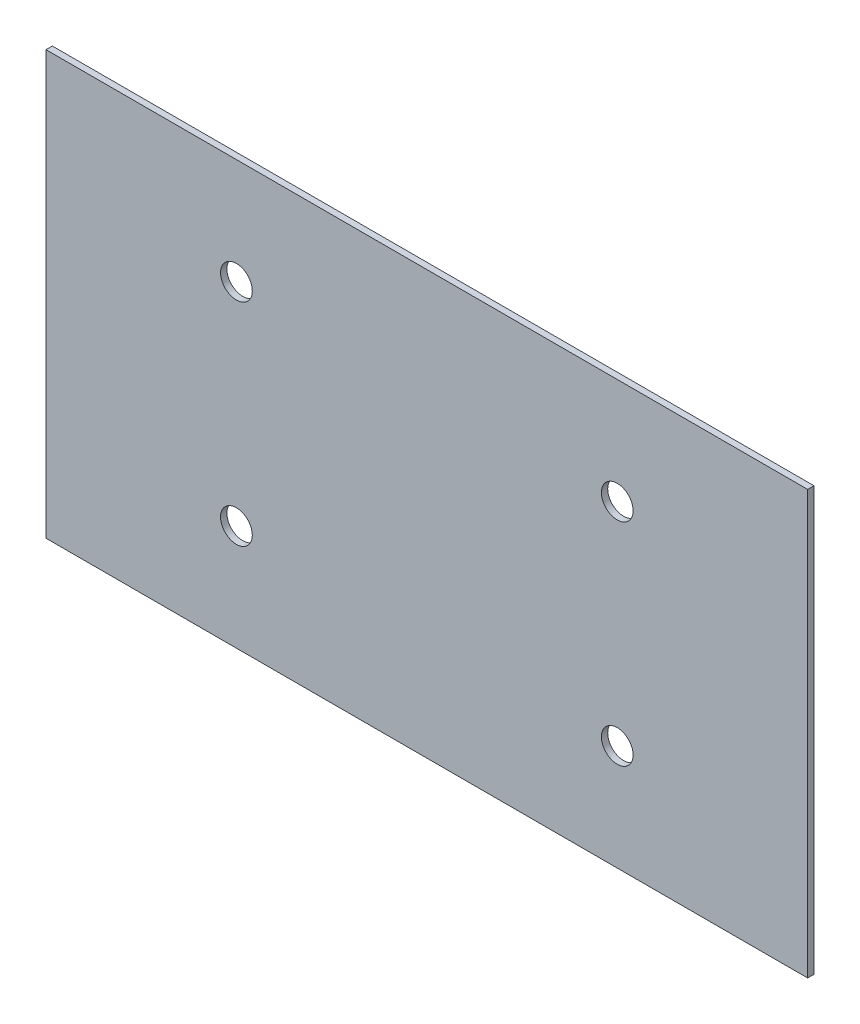
SolidWorks part; units mm, degrees
ref_plane "Alzado" through (0, 0, 0) normal (0, 0, 1) x (1, 0, 0)
ref_plane "Planta" through (0, 0, 0) normal (0, 1, 0) x (1, 0, 0)
ref_plane "Vista lateral" through (0, 0, 0) normal (1, 0, 0) x (0, 0, -1)
sketch "Croquis1" plane through (0, 0, 0) normal (0, 0, 1) x (1, 0, 0)
  line L1 (-180, 100) -> (180, 100)
  line L2 (-180, 100) -> (-180, -100)
  line L3 (-180, -100) -> (180, -100)
  line L4 (180, 100) -> (180, -100)
  line L5 (-180, 100) -> (180, -100) construction
  line L6 (-180, -100) -> (180, 100) construction
  point P0 (0, 0)
  dimension "D1" = 360
  dimension "D2" = 200
extrude "Saliente-Extruir1" add sketch "Croquis1" along normal blind 3
sketch "Croquis2" plane through (0, 0, 0) normal (0, 0, -1) x (-1, 0, 0)
  line L0 (0, 100) -> (0, -100) construction
  line L1 (-180, 100) -> (180, 100) construction
  line L2 (180, -100) -> (-180, -100) construction
  line L10 (-180, 0) -> (180, 0) construction
  line L11 (-180, -100) -> (-180, 100) construction
  line L12 (180, 100) -> (180, -100) construction
  circle A0 centre (-90, 50) radius 7.5
  circle A1 centre (90, 50) radius 7.5
  circle A2 centre (90, -50) radius 7.5
  circle A3 centre (-90, -50) radius 7.5
  dimension "D1" = 15
  dimension "D3" = 50
  dimension "D2" = 90
  dimension "D5" = 2
  dimension "D4" = 2
extrude "Cortar-Extruir1" cut sketch "Croquis2" against normal blind 10
equation "\"largo\"= 330mm"
equation "\"ancho\"= 200mm"
